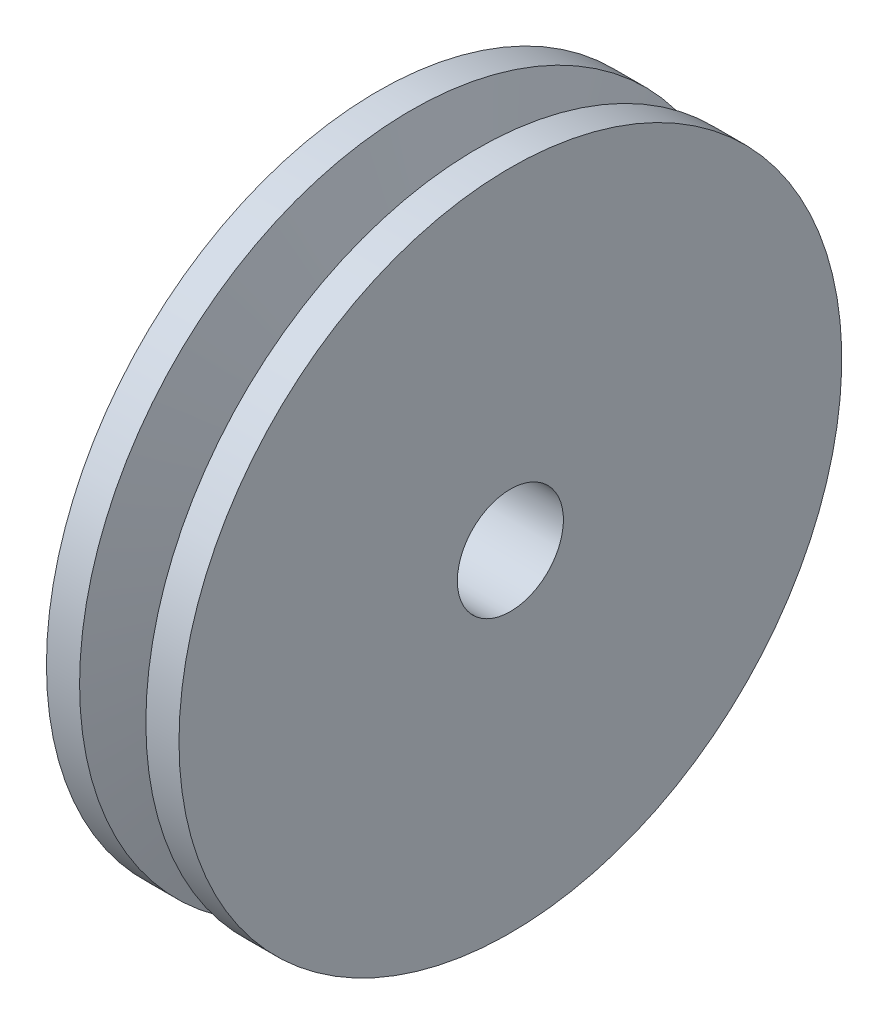
SolidWorks part; units mm, degrees
ref_plane "Front Plane" through (0, 0, 0) normal (0, 0, 1) x (1, 0, 0)
ref_plane "Top Plane" through (0, 0, 0) normal (0, 1, 0) x (1, 0, 0)
ref_plane "Right Plane" through (0, 0, 0) normal (1, 0, 0) x (0, 0, -1)
sketch "Sketch1" plane through (0, 0, 0) normal (0, 1, 0) x (1, 0, 0)
  line L0 (0, 13.4792) -> (0, -12.4792) construction
  line L1 (-18.9583, 0) -> (20.7083, 0) construction
  line L2 (5, 0) -> (-5, 0)
  line L3 (-5, 0) -> (-5, 25)
  line L4 (-5, 25) -> (-2.5, 25)
  line L5 (-2.5, 25) -> (0, 15)
  line L6 (2.5, 25) -> (0, 15)
  line L7 (5, 25) -> (2.5, 25)
  line L8 (5, 0) -> (5, 25)
  point P13 (0, 0)
  dimension "D1" = 5
  dimension "D2" = 25
  dimension "D3" = 2.5
  dimension "D4" = 15
revolve "Revolve1" add sketch "Sketch1" angle 360 about L1
sketch "Sketch2" plane through (-5, 0, 0) normal (-1, 0, 0) x (0, 0, 1)
  circle A0 centre (0, 0) radius 4
  dimension "D1" = 8
extrude "Cut-Extrude1" cut sketch "Sketch2" against normal blind 10
